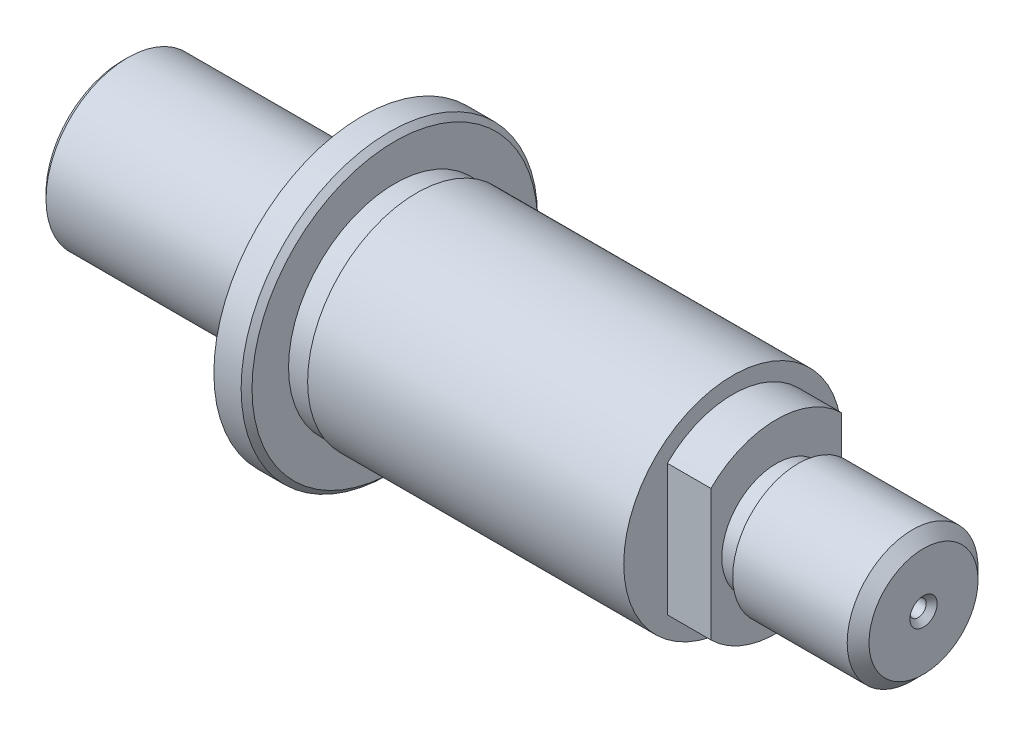
SolidWorks part; units mm, degrees
ref_plane "Plan de face" through (0, 0, 0) normal (0, 0, 1) x (1, 0, 0)
ref_plane "Plan de dessus" through (0, 0, 0) normal (0, 1, 0) x (1, 0, 0)
ref_plane "Plan de droite" through (0, 0, 0) normal (1, 0, 0) x (0, 0, -1)
sketch "Esquisse1" plane through (0, 0, 0) normal (0, 0, 1) x (1, 0, 0)
  line L0 (0, 0) -> (93.6052, 0) construction
  line L1 (0, 0) -> (0, 5)
  line L2 (0, 5) -> (6, 5)
  line L3 (6, 5) -> (6, 4.75)
  line L4 (6, 4.75) -> (8, 4.75)
  line L5 (8, 4.75) -> (8, 7.5)
  line L6 (8, 7.5) -> (22, 7.5)
  line L7 (22, 7.5) -> (22, 13.6)
  line L8 (22, 13.6) -> (25, 13.6)
  line L9 (25, 13.6) -> (25, 9.75)
  line L10 (25, 9.75) -> (27, 9.75)
  line L11 (27, 9.75) -> (27, 10)
  line L12 (27, 10) -> (56, 10)
  line L13 (56, 10) -> (56, 8.5)
  line L14 (56, 8.5) -> (60, 8.5)
  line L15 (60, 8.5) -> (60, 5)
  line L16 (60, 5) -> (62, 5)
  line L17 (62, 5) -> (62, 6)
  line L18 (62, 6) -> (73.5, 6)
  line L19 (73.5, 6) -> (73.5, 0)
  line L20 (73.5, 0) -> (0, 0)
  dimension "D1" = 9.5
  dimension "D2" = 10
  dimension "D3" = 15
  dimension "D4" = 27.2
  dimension "D5" = 20
  dimension "D6" = 19.5
  dimension "D7" = 17
  dimension "D8" = 12
  dimension "D9" = 10
  dimension "D10" = 73.5
  dimension "D11" = 6
  dimension "D12" = 8
  dimension "D13" = 14
  dimension "D14" = 31
  dimension "D15" = 2
  dimension "D16" = 48
  dimension "D17" = 4
  dimension "D18" = 2
revolve "Révolution1" add sketch "Esquisse1" angle 360 about L0
cosmetic thread "Représentation de filetage1" parameters "D1"=11.5, "D2"=10
chamfer "Chanfrein1" distance 0.5 angle 45 4 edges at (8, 0, 7.5) (8, 0, 4.75) (0, 0, 5) (25, 0, 13.6)
sketch "Esquisse2" plane through (60, 0, 0) normal (1, 0, 0) x (0, 0, -1)
  line L0 (0, 0) -> (0, 9.2784) construction
  line L1 (-6, 12.5735) -> (-6, -12.5735)
  line L2 (6, 12.5735) -> (6, -12.5735)
  arc A0 (-6, 12.5735) -> (-6, -12.5735) centre (0, 0) ccw
  arc A1 (6, -12.5735) -> (6, 12.5735) centre (0, 0) ccw
  dimension "D1" = 12
extrude "Enlèv. mat.-Extru.1" cut sketch "Esquisse2" against normal up to surface (4 mm away) up to face at (56, 0, 10)
chamfer "Chanfrein2" distance 1 angle 45 1 edges at (73.5, 0, 6)
hole_wizard "Diamètre du perçage Ø1.5 (1.5)1" positions "Esquisse4" profile "Esquisse3" hole size "Ø1.5" standard "ISO"
sketch "Esquisse4" plane through (73.5, 0, 0) normal (1, 0, 0) x (0, 0, -1)
  circle A0 centre (0, 0) radius 5 construction
  point P0 (0, 0)
sketch "Esquisse3" plane through (73.5, 0, 0) normal (0, 1, 0) x (0, 0, -1)
  line L0 (0, 0) -> (0, 2.4506)
  line L1 (0, 2.4506) -> (0.75, 2)
  line L2 (0.75, 2) -> (0.75, 0)
  line L5 (0.75, 0) -> (0, 0)
  line L10 (0, 2.4506) -> (-0.75, 2) construction
  line L11 (0, -6.35) -> (0, 107.95) construction
  dimension "Diamètre du perçage" = 1.5
  dimension "Profondeur du perçage" = 2
  dimension "Angle de pointe" = 118
chamfer "Chanfrein3" distance 0.5 angle 45 1 edges at (73.5, 0, -0.75)
hole_wizard "Diamètre du perçage Ø1.5 (1.5)2" positions "Esquisse6" profile "Esquisse5" hole size "Ø1.5" standard "ISO"
sketch "Esquisse6" plane through (0, 0, 0) normal (-1, 0, 0) x (0, 0, 1)
  point P0 (0, 0)
sketch "Esquisse5" plane through (0, 0, 0) normal (0, 1, 0) x (0, 0, 1)
  line L0 (0, 0) -> (0, 2.4506)
  line L1 (0, 2.4506) -> (0.75, 2)
  line L2 (0.75, 2) -> (0.75, 0)
  line L5 (0.75, 0) -> (0, 0)
  line L10 (0, 2.4506) -> (-0.75, 2) construction
  line L11 (0, -6.35) -> (0, 107.95) construction
  dimension "Diamètre du perçage" = 1.5
  dimension "Profondeur du perçage" = 2
  dimension "Angle de pointe" = 118
chamfer "Chanfrein4" distance 0.5 angle 45 1 edges at (0, 0, 0.75)
ref_plane "Plan1" through (0, 4.5, 0) normal (0, 1, 0) x (-1, 0, 0)
sketch "Esquisse8" [suppressed] plane through (0, 0, 0) normal (0, 0, 1) x (1, 0, 0)
  line L0 (22, 13.6) -> (22, -13.6) construction
  line L1 (22, 8.9404) -> (22, 2.9686)
  spline S0 degree 3 poles (22, 2.9686) (18.941, 4.0087) (10.6114, -0.3272) (8.8657, 5.5933) (9.2703, 10.1572) (16.45, 8.5414) (20.142, 9.784) (22, 8.9404) knots 0 0 0 0 0.409715 0.486452 0.574881 0.811372 1 1 1 1
extrude "Enlèv. mat.-Extru.3" [suppressed] cut sketch "Esquisse8" against normal through all
sketch "Esquisse9" plane through (0, 0, 0) normal (-1, 0, 0) x (0, 0, 1)
  circle A0 centre (0, 0) radius 7.5 construction
  circle A1 centre (0, 0) radius 7.5
  circle A2 centre (0, 0) radius 4.5 construction
  circle A3 centre (0, 0) radius 4.5
extrude "Boss.-Extru.1" add sketch "Esquisse9" against normal up to next
chamfer "Chanfrein5" distance 0.5 angle 45 1 edges at (0, 0, 7.5)
